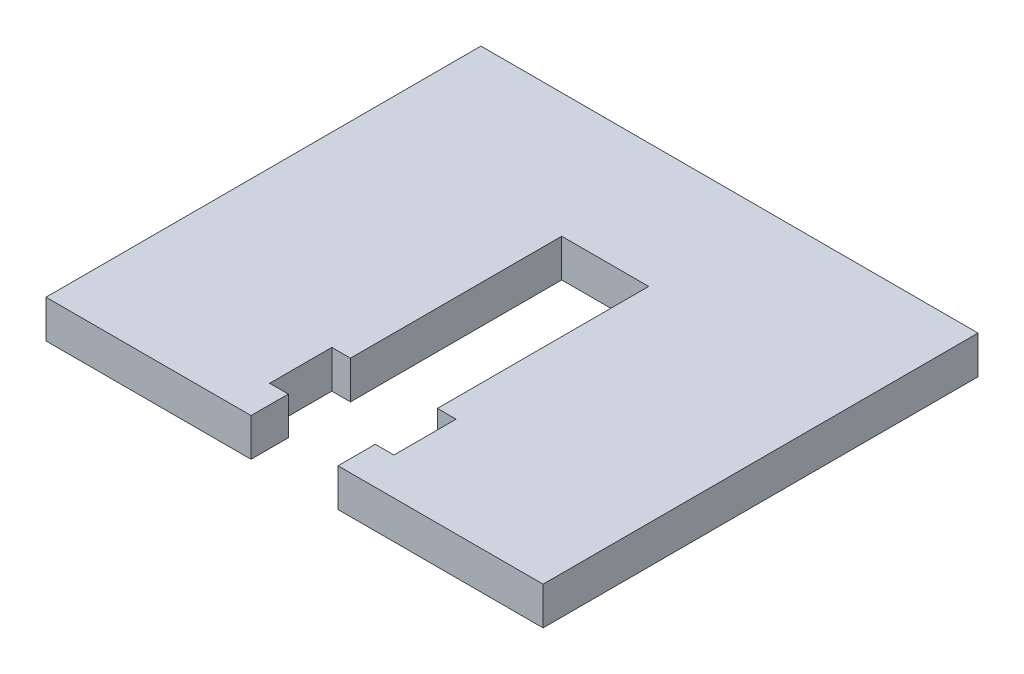
SolidWorks part; units mm, degrees
ref_plane "Front Plane" through (0, 0, 0) normal (0, 0, 1) x (1, 0, 0)
ref_plane "Top Plane" through (0, 0, 0) normal (0, 1, 0) x (1, 0, 0)
ref_plane "Right Plane" through (0, 0, 0) normal (1, 0, 0) x (0, 0, -1)
sketch "Sketch1" plane through (0, 0, 0) normal (0, 1, 0) x (1, 0, 0)
  line L0 (0, 0) -> (0, 35)
  line L1 (0, 35) -> (40, 35)
  line L2 (40, 35) -> (40, 0)
  line L3 (40, 0) -> (23.5, 0)
  line L4 (23.5, 0) -> (23.5, 3)
  line L5 (23.5, 3) -> (25, 3)
  line L6 (25, 3) -> (25, 8)
  line L7 (25, 8) -> (23.5, 8)
  line L8 (23.5, 8) -> (23.5, 25)
  line L9 (23.5, 25) -> (16.5, 25)
  line L10 (16.5, 25) -> (16.5, 8)
  line L11 (16.5, 8) -> (15, 8)
  line L12 (15, 8) -> (15, 3)
  line L13 (15, 3) -> (16.5, 3)
  line L14 (16.5, 3) -> (16.5, 0)
  line L15 (16.5, 0) -> (0, 0)
  dimension "D1" = 35
  dimension "D2" = 16.5
  dimension "D3" = 16.5
  dimension "D4" = 40
  dimension "D5" = 1.5
  dimension "D6" = 5
  dimension "D7" = 1.5
  dimension "D8" = 3
  dimension "D9" = 17
  dimension "D10" = 17
  dimension "D11" = 1.5
  dimension "D12" = 5
  dimension "D13" = 1.5
extrude "Boss-Extrude1" add sketch "Sketch1" along normal blind 3.05
